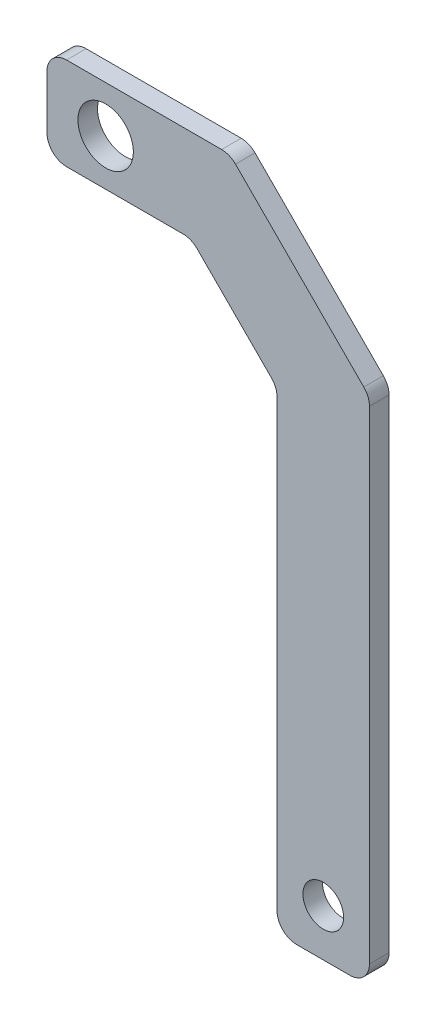
SolidWorks part; units mm, degrees
material "3003-H14"
ref_plane "X-Y Datum" through (0, 0, 0) normal (0, 0, 1) x (1, 0, 0)
ref_plane "X-Z Datum" through (0, 0, 0) normal (0, 1, 0) x (1, 0, 0)
ref_plane "Y-Z Datum" through (0, 0, 0) normal (1, 0, 0) x (0, 0, -1)
sketch "Sketch2" plane through (0, 0, 0) normal (0, 0, 1) x (1, 0, 0)
  line L0 (-183.3727, 213.9142) -> (-183.3727, 213.123) construction
  line L1 (-174.6351, 213.123) -> (-174.6351, 213.9142) construction
  line L2 (-183.3727, 213.9142) -> (-183.3727, 213.123) construction
  line L3 (-174.6351, 213.123) -> (-174.6351, 213.9142) construction
  line L4 (-183.3727, 213.5186) -> (-174.6351, 213.5186) construction
  line L5 (-179.0039, 221.0186) -> (-179.0039, 206.0186) construction
  line L6 (-151.1879, 122.9864) -> (-136.1879, 122.9864) construction
  line L7 (-179.0039, 206.0186) -> (-188.5289, 206.0186)
  line L8 (-188.5289, 206.0186) -> (-188.5289, 221.0186)
  line L9 (-188.5289, 221.0186) -> (-179.0039, 221.0186)
  line L10 (-151.1879, 122.9864) -> (-151.1879, 115.3664)
  line L11 (-151.1879, 115.3664) -> (-136.1879, 115.3664)
  line L12 (-136.1879, 115.3664) -> (-136.1879, 122.9864)
  line L13 (-179.0039, 206.0186) -> (-151.1879, 206.0186)
  line L14 (-151.1879, 206.0186) -> (-151.1879, 122.9864)
  line L15 (-136.1879, 122.9864) -> (-136.1879, 198.2423)
  line L16 (-158.8632, 221.0186) -> (-179.0039, 221.0186)
  line L17 (-165.0959, 206.0186) -> (-151.1879, 192.0486)
  line L18 (-136.1879, 198.2423) -> (-158.8632, 221.0186)
  circle A0 centre (-143.6879, 122.9864) radius 3 construction
  circle A1 centre (-143.6879, 122.9864) radius 3 construction
  arc A2 (-183.3727, 213.123) -> (-174.6351, 213.123) centre (-179.0039, 213.123) ccw construction
  arc A3 (-183.3727, 213.123) -> (-174.6351, 213.123) centre (-179.0039, 213.123) ccw construction
  arc A4 (-174.6351, 213.9142) -> (-183.3727, 213.9142) centre (-179.0039, 213.9142) ccw construction
  arc A5 (-174.6351, 213.9142) -> (-183.3727, 213.9142) centre (-179.0039, 213.9142) ccw construction
  point P14 (-179.0039, 213.5186)
  point P16 (-143.6879, 122.9864)
  point P27 (-136.1879, 198.2122)
  dimension "D1" = 15
  dimension "D2" = 15
  dimension "D3" = 9.525
  dimension "D4" = 7.62
  dimension "D5" = 13.908
  dimension "D6" = 13.97
  dimension "D7" = 15
extrude "Boss-Extrude1" add sketch "Sketch2" along normal blind 3.175 contours L15 L18 L16 L9 L8 L7 L13 L14 L10 L11 L12 | L13 L17 L14
hole_wizard "M6 Clearance Hole1" positions "Sketch4" profile "Sketch5" hole size "M6" standard "ANSI Metric" end condition through all
sketch "Sketch4" plane through (0, 0, 3.175) normal (0, 0, 1) x (1, 0, 0)
  point P0 (-143.6879, 122.9864)
sketch "Sketch5" plane through (-143.6879, 122.9864, 3.175) normal (1, 0, 0) x (0, -1, 0)
  line L0 (0, 0) -> (0, 3.175)
  line L1 (0, 3.175) -> (3.3, 3.175)
  line L2 (3.3, 3.175) -> (3.3, 0)
  line L5 (3.3, 0) -> (0, 0)
  line L11 (0, -6.35) -> (0, 107.95) construction
  dimension "Thru Hole Dia." = 6.6
  dimension "Thru Hole Depth" = 3.175
fillet "Fillet1" radius 3.175 8 edges at (-151.1879, 192.0486, 1.5875) (-165.0959, 206.0186, 1.5875) (-158.8632, 221.0186, 1.5875) (-136.1879, 198.2423, 1.5875) (-188.5289, 221.0186, 1.5875) (-188.5289, 206.0186, 1.5875) (-151.1879, 115.3664, 1.5875) (-136.1879, 115.3664, 1.5875)
hole_wizard "M8 Clearance Hole1" positions "Sketch6" profile "Sketch7" hole size "M8" standard "ANSI Metric" end condition through all
sketch "Sketch6" plane through (0, 0, 3.175) normal (0, 0, 1) x (1, 0, 0)
  point P0 (-179.0039, 213.5186)
sketch "Sketch7" plane through (-179.0039, 213.5186, 3.175) normal (1, 0, 0) x (0, -1, 0)
  line L0 (0, 0) -> (0, 3.175)
  line L1 (0, 3.175) -> (4.5, 3.175)
  line L2 (4.5, 3.175) -> (4.5, 0)
  line L5 (4.5, 0) -> (0, 0)
  line L11 (0, -6.35) -> (0, 107.95) construction
  dimension "Thru Hole Dia." = 9
  dimension "Thru Hole Depth" = 3.175
